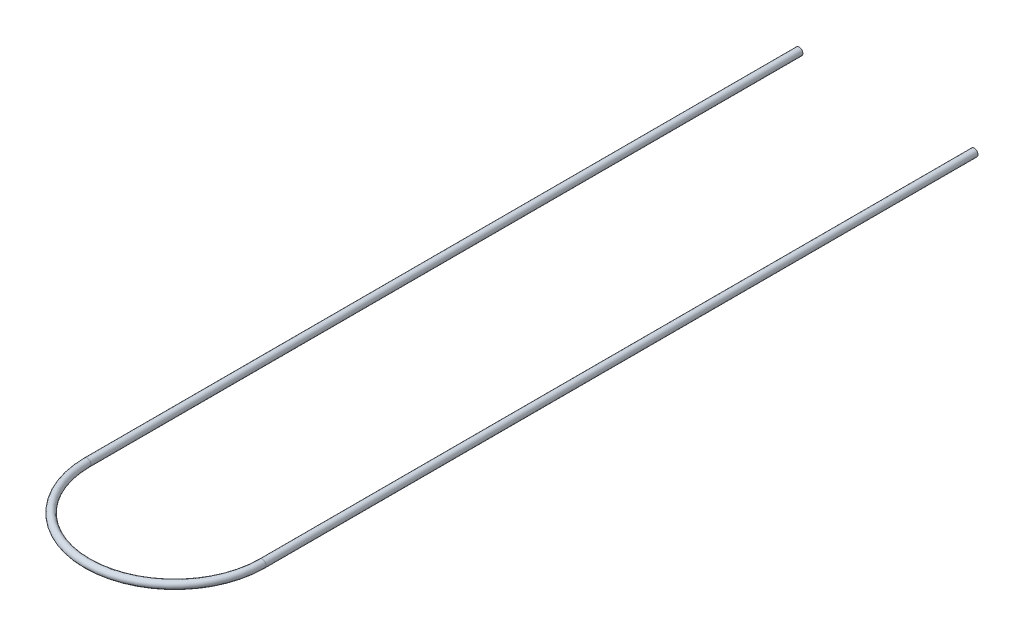
SolidWorks part; units mm, degrees
ref_plane "Front Plane" through (0, 0, 0) normal (0, 0, 1) x (1, 0, 0)
ref_plane "Top Plane" through (0, 0, 0) normal (0, 1, 0) x (1, 0, 0)
ref_plane "Right Plane" through (0, 0, 0) normal (1, 0, 0) x (0, 0, -1)
sketch "Sketch1" plane through (0, 0, 0) normal (0, 1, 0) x (1, 0, 0)
  line L0 (486.47, -300) -> (486.47, -2440)
  line L2 (-40, -300) -> (-40, -2440)
  arc A0 (-40, -2440) -> (486.47, -2440) centre (223.235, -2440) ccw
  dimension "D1" = 2140
  dimension "D2" = 526.47
ref_plane "Plane1" through (486.47, 0, 300) normal (0, 0, -1) x (-1, 0, 0)
sketch "Sketch2" plane through (486.47, 0, 300) normal (0, 0, -1) x (-1, 0, 0)
  circle A0 centre (0, 0) radius 9.95
  circle A1 centre (0, 0) radius 11.1
  dimension "D1" = 22.2
  dimension "D2" = 19.9
sweep "Sweep1" add profiles "Sketch2" path "Sketch1"
